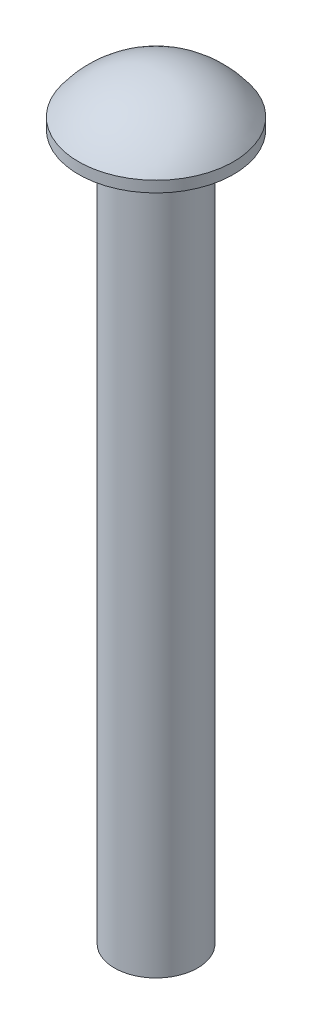
SolidWorks part; units mm, degrees
ref_plane "Front Plane" through (0, 0, 0) normal (0, 0, 1) x (1, 0, 0)
ref_plane "Top Plane" through (0, 0, 0) normal (0, 1, 0) x (1, 0, 0)
ref_plane "Right Plane" through (0, 0, 0) normal (1, 0, 0) x (0, 0, -1)
sketch "Sketch1" plane through (0, 0, 0) normal (0, 0, 1) x (1, 0, 0)
  line L0 (0, 0) -> (-1.5, 0)
  line L1 (-1.5, 0) -> (-1.5, 25.4)
  line L2 (-1.5, 25.4) -> (-2.794, 25.4)
  line L3 (-2.794, 25.4) -> (-2.794, 25.7969)
  line L7 (0, 0) -> (0, 27.2395) construction
  line L8 (0, 0) -> (0, 27.2395)
  arc A0 (-2.794, 25.7969) -> (0, 27.2395) centre (0, 23.8125) cw
  point P0 (-1.5, 25.5198)
  dimension "D1" = 3
  dimension "D2" = 5.588
  dimension "D3" = 0.3969
  dimension "D4" = 25.4
  dimension "D5" = 23.8125
revolve "Revolve1" add sketch "Sketch1" angle 360 about L7
